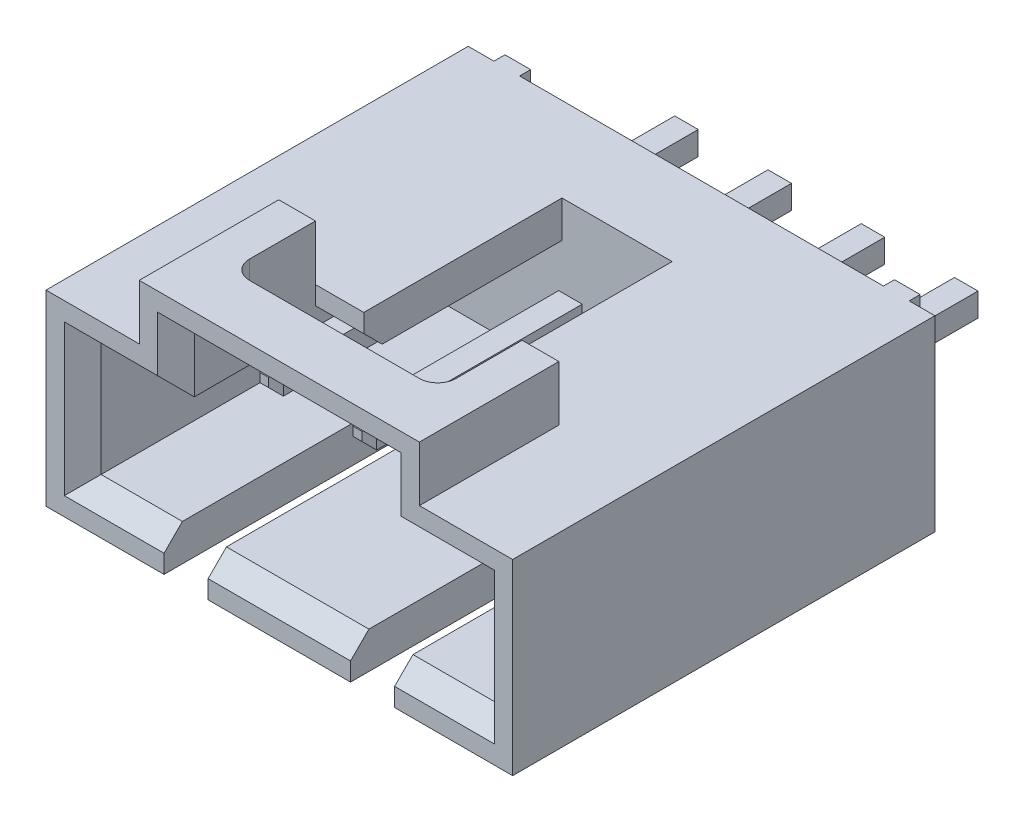
SolidWorks part; units mm, degrees
ref_plane "Front" through (0, 0, 0) normal (0, 0, 1) x (1, 0, 0)
ref_plane "Top" through (0, 0, 0) normal (0, 1, 0) x (1, 0, 0)
ref_plane "Right" through (0, 0, 0) normal (1, 0, 0) x (0, 0, -1)
sketch "Эскиз1" plane through (0, 0, 0) normal (0, 1, 0) x (1, 0, 0)
  line L0 (-4.955, -0.3) -> (4.955, -0.3)
  line L1 (4.955, -0.3) -> (4.955, 0)
  line L2 (4.955, 0) -> (5.655, 0)
  line L3 (5.655, 0) -> (5.655, -0.3)
  line L4 (5.655, -0.3) -> (6.355, -0.3)
  line L5 (6.355, -0.3) -> (6.355, -11.8)
  line L6 (6.355, -11.8) -> (-6.355, -11.8)
  line L7 (-6.355, -11.8) -> (-6.355, -0.3)
  line L8 (-6.355, -0.3) -> (-5.655, -0.3)
  line L9 (-5.655, -0.3) -> (-5.655, 0)
  line L10 (-5.655, 0) -> (-4.955, 0)
  line L11 (-4.955, 0) -> (-4.955, -0.3)
  line L12 (0, -0.3) -> (0, 0) construction
  line L13 (0, -11.8) -> (0, -0.3) construction
  dimension "D2" = 12.71
  dimension "D3" = 0.7
  dimension "D1" = 11.8
  dimension "D4" = 0.3
  dimension "D5" = 0.7
extrude "Бобышка-Вытянуть1" add sketch "Эскиз1" along normal mid plane 5.1
sketch "Эскиз2" plane through (0, 0, 11.8) normal (0, 0, 1) x (1, 0, 0)
  line L0 (-5.355, 1.55) -> (-5.355, -1.55)
  line L2 (5.355, -1.55) -> (5.355, 1.55)
  line L3 (5.355, 1.55) -> (1.5, 1.55)
  line L4 (1.5, 1.55) -> (1.5, 2.55)
  line L5 (-5.355, -1.55) -> (-3.14, -1.55)
  line L6 (1.5, 2.55) -> (-1.5, 2.55)
  line L7 (-1.5, 2.55) -> (-1.5, 1.55)
  line L8 (-1.5, 1.55) -> (-5.355, 1.55)
  line L9 (5.355, -1.55) -> (3.14, -1.55)
  line L10 (3.14, -1.55) -> (3.14, -2.55)
  line L11 (-6.355, -2.55) -> (6.355, -2.55) construction
  line L12 (3.14, -2.55) -> (1.94, -2.55)
  line L13 (1.94, -2.55) -> (1.94, -1.55)
  line L15 (5.355, 1.55) -> (6.355, 1.55) construction
  line L16 (6.355, 2.55) -> (6.355, -2.55) construction
  line L17 (-5.355, 1.55) -> (-6.355, 1.55) construction
  line L18 (-6.355, 2.55) -> (-6.355, -2.55) construction
  line L19 (-6.355, 2.55) -> (6.355, 2.55) construction
  line L20 (-3.14, -1.55) -> (-3.14, -2.55)
  line L21 (-3.14, -2.55) -> (-1.94, -2.55)
  line L22 (-1.94, -2.55) -> (-1.94, -1.55)
  line L23 (-1.94, -1.55) -> (1.94, -1.55)
  point P7 (0, 2.55)
  point P8 (0, 2.55)
  point P20 (2.54, -2.55)
  point P23 (-3.14, -1.55)
  dimension "D1" = 1.2
  dimension "D2" = 3
  dimension "D3" = 1
  dimension "D4" = 3.815
extrude "Вырез-Вытянуть1" cut sketch "Эскиз2" against normal offset from surface (9.2 mm away) 2.3 up to face at (0, 0, 0.3)
sketch "Эскиз3" plane through (0, 0, 11.8) normal (0, 0, 1) x (1, 0, 0)
  line L0 (-3.815, 2.55) -> (-3.815, 4.05)
  line L1 (-6.355, 2.55) -> (-1.5, 2.55) construction
  line L2 (-3.815, 4.05) -> (3.815, 4.05)
  line L3 (3.815, 4.05) -> (3.815, 2.55)
  line L5 (3.815, 2.55) -> (2.815, 2.55)
  line L6 (2.815, 2.55) -> (2.815, 3.05)
  line L7 (2.815, 3.05) -> (-2.815, 3.05)
  line L8 (-2.815, 3.05) -> (-2.815, 2.55)
  line L9 (-2.815, 2.55) -> (-3.815, 2.55)
  line L10 (0, 0) -> (0, 3.05) construction
  line L11 (0, 3.05) -> (0, 4.05) construction
  line L12 (2.815, 1.55) -> (2.815, 2.55) construction
  line L15 (1.5, 2.55) -> (6.355, 2.55) construction
  line L16 (5.355, 1.55) -> (1.5, 1.55) construction
  line L17 (3.14, -2.55) -> (6.355, -2.55) construction
  dimension "D1" = 7.63
  dimension "D2" = 6.6
extrude "Бобышка-Вытянуть2" add sketch "Эскиз3" against normal blind 3.8
sketch "Эскиз4" plane through (0, 0, 11.8) normal (0, 0, 1) x (1, 0, 0)
  line L0 (-2.815, 2.55) -> (-2.815, 1.55)
  line L1 (-1.5, 1.55) -> (-5.355, 1.55) construction
  line L2 (-2.815, 1.55) -> (2.815, 1.55)
  line L3 (5.355, 1.55) -> (1.5, 1.55) construction
  line L4 (2.815, 1.55) -> (2.815, 2.55)
  line L5 (2.815, 2.55) -> (-2.815, 2.55)
extrude "Вырез-Вытянуть2" cut sketch "Эскиз4" against normal up to surface (3.8 mm away) up to face at (0, 3.05, 8)
sketch "Эскиз5" plane through (0, 4.05, 0) normal (0, 1, 0) x (1, 0, 0)
  line L0 (2.815, -8) -> (2.815, -9.8)
  line L1 (3.815, -8) -> (-3.815, -8) construction
  line L2 (2.315, -10.3) -> (-2.315, -10.3)
  line L3 (-2.815, -9.8) -> (-2.815, -8)
  line L4 (-2.815, -8) -> (2.815, -8)
  line L5 (3.815, -11.8) -> (-3.815, -11.8) construction
  arc A0 (2.815, -9.8) -> (2.315, -10.3) centre (2.315, -9.8) cw
  arc A1 (-2.315, -10.3) -> (-2.815, -9.8) centre (-2.315, -9.8) cw
  dimension "D1" = 1.5
  dimension "D2" = 0.5
extrude "Вырез-Вытянуть3" cut sketch "Эскиз5" against normal up to next
chamfer "Фаска1" distance 0.5 angle 45 12 edges at (4.2475, -1.55, 11.8) (5.355, 0, 11.8) (4.085, 1.55, 11.8) (2.815, 2.3, 11.8) (-5.355, 0, 11.8) (-4.085, 1.55, 11.8) (-2.815, 2.3, 11.8) (0, 3.05, 11.8) (-2.1575, 1.55, 8) (2.1575, 1.55, 8) (0, -1.55, 11.8) (-4.2475, -1.55, 11.8)
sketch "Эскиз6" plane through (0, 0, 0.3) normal (0, 0, 1) x (1, 0, 0)
  line L0 (0, 0) -> (3.81, 0) construction
  line L1 (4.13, -0.32) -> (3.49, -0.32)
  line L2 (4.13, -0.32) -> (4.13, 0.32)
  line L3 (4.13, 0.32) -> (3.49, 0.32)
  line L4 (3.49, -0.32) -> (3.49, 0.32)
  line L5 (4.13, -0.32) -> (3.49, 0.32) construction
  line L6 (4.13, 0.32) -> (3.49, -0.32) construction
  line L7 (6.355, 2.55) -> (6.355, -2.55) construction
  point P0 (3.81, 0)
  dimension "D1" = 0.64
  dimension "D2" = 0.64
  dimension "D3" = 2.545
extrude "Бобышка-Вытянуть3" add sketch "Эскиз6" along normal offset from surface 3.4 and the other way offset from surface (3.6 mm away) 3.3 up to face at (0, 0.76, 11.8) other way up to face at (5.305, 0, 0)
chamfer "Фаска2" distance 0.2 angle 45 8 edges at (3.49, 0, 8.4) (3.81, 0.32, 8.4) (4.13, 0, 8.4) (3.81, -0.32, 8.4) (3.81, -0.32, -3.3) (4.13, 0, -3.3) (3.81, 0.32, -3.3) (3.49, 0, -3.3)
pattern_linear "Линейный массив1" count 4 spacing 2.54 along (-1, 0, 0) of "Бобышка-Вытянуть3", "Фаска2"
equation "\"Pins\"= 4"
equation "\"B\"= \"Pins\" * 2.54мм + 2.55мм"
equation "\"D2@Эскиз1\"= \"B\""
equation "\"D1@Линейный массив1\"= \"Pins\""
